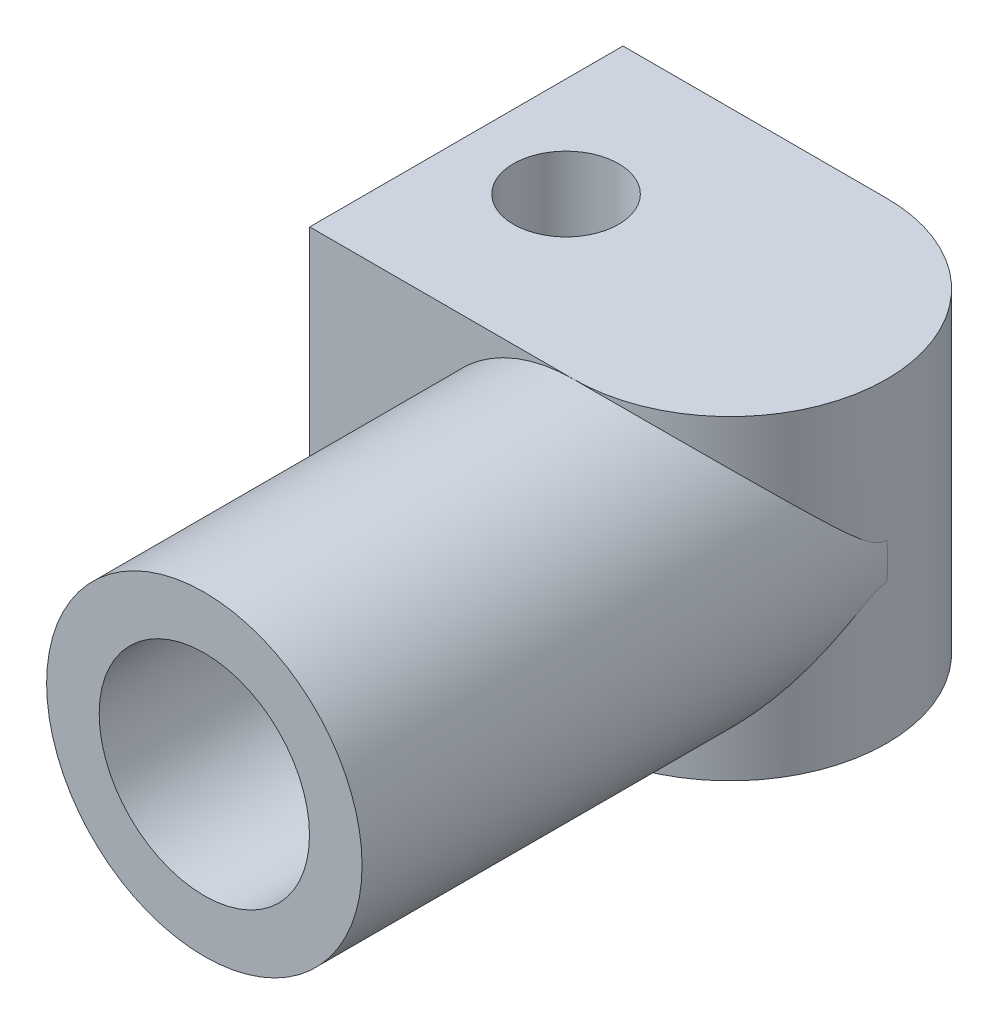
SolidWorks part; units mm, degrees
ref_plane "Front Plane" through (0, 0, 0) normal (0, 0, 1) x (1, 0, 0)
ref_plane "Top Plane" through (0, 0, 0) normal (0, 1, 0) x (1, 0, 0)
ref_plane "Right Plane" through (0, 0, 0) normal (1, 0, 0) x (0, 0, -1)
sketch "Sketch1" plane through (0, 0, 0) normal (0, 0, 1) x (1, 0, 0)
  circle A0 centre (0, 0) radius 5
  circle A1 centre (0, 0) radius 7.5
  dimension "D1" = 10
  dimension "D2" = 15
extrude "Boss-Extrude1" add sketch "Sketch1" along normal blind 25
sketch "Sketch4" plane through (0, 0, 0) normal (0, 1, 0) x (1, 0, 0)
  line L0 (0, 0) -> (-9.305, 0) construction
  line L1 (0, -7.4494) -> (-9.305, -7.4494)
  line L2 (0, 7.4494) -> (-9.305, 7.4494)
  line L3 (-9.305, -7.4494) -> (-12.5416, -7.4494)
  line L4 (-12.5416, -7.4494) -> (-12.5416, 7.4494)
  line L5 (-12.5416, 7.4494) -> (-9.305, 7.4494)
  arc A0 (0, -7.4494) -> (0, 7.4494) centre (0, 0) ccw
  point P3 (-4.6525, 0)
extrude "Boss-Extrude3" add sketch "Sketch4" along normal mid plane 15
sketch "Sketch5" plane through (0, 7.5, 0) normal (0, 1, 0) x (1, 0, 0)
  circle A0 centre (-7.8, 0) radius 2.5
  dimension "D1" = 5
  dimension "D2" = 7.8
extrude "Cut-Extrude3" cut sketch "Sketch5" against normal blind 15
